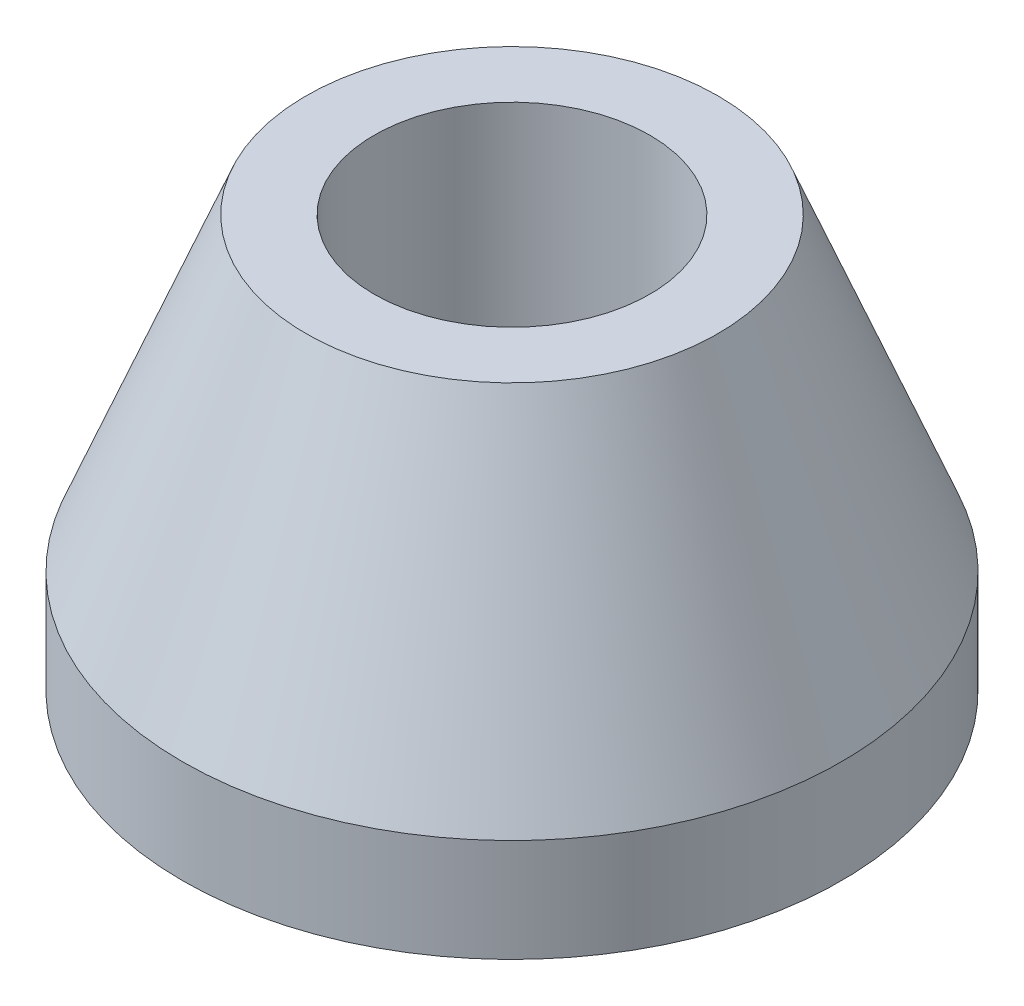
SolidWorks part; units mm, degrees
ref_plane "Front Plane" through (0, 0, 0) normal (0, 0, 1) x (1, 0, 0)
ref_plane "Top Plane" through (0, 0, 0) normal (0, 1, 0) x (1, 0, 0)
ref_plane "Right Plane" through (0, 0, 0) normal (1, 0, 0) x (0, 0, -1)
sketch "Sketch2" plane through (0, 0, 0) normal (1, 0, 0) x (0, 0, -1)
  line L0 (0, 0) -> (-6.35, 0)
  line L1 (-6.35, 0) -> (-10.16, -9.525)
  line L2 (-10.16, -9.525) -> (-10.16, -12.7)
  line L3 (-10.16, -12.7) -> (0, -12.7)
  line L4 (0, -12.7) -> (0, 0)
  dimension "D1" = 6.35
  dimension "D2" = 10.16
  dimension "D3" = 12.7
  dimension "D4" = 3.175
revolve "Revolve1" add sketch "Sketch2" angle 360 about L4
sketch "Sketch6" plane through (0, 0, 0) normal (0, 1, 0) x (1, 0, 0)
  circle A0 centre (0, 0) radius 4.25
  dimension "D1" = 8.5
extrude "Cut-Extrude3" cut sketch "Sketch6" against normal through all
sketch "Sketch7" plane through (0, -12.7, 0) normal (0, -1, 0) x (1, 0, 0)
  line L1 (0, 7.2746) -> (-6.3, 3.6373)
  line L2 (-6.3, 3.6373) -> (-6.3, -3.6373)
  line L3 (-6.3, -3.6373) -> (0, -7.2746)
  line L4 (0, -7.2746) -> (6.3, -3.6373)
  line L5 (6.3, -3.6373) -> (6.3, 3.6373)
  line L6 (6.3, 3.6373) -> (0, 7.2746)
  circle A0 centre (0, 0) radius 6.3 construction
  dimension "D1" = 12.6
extrude "Cut-Extrude4" cut sketch "Sketch7" against normal blind 6.35
